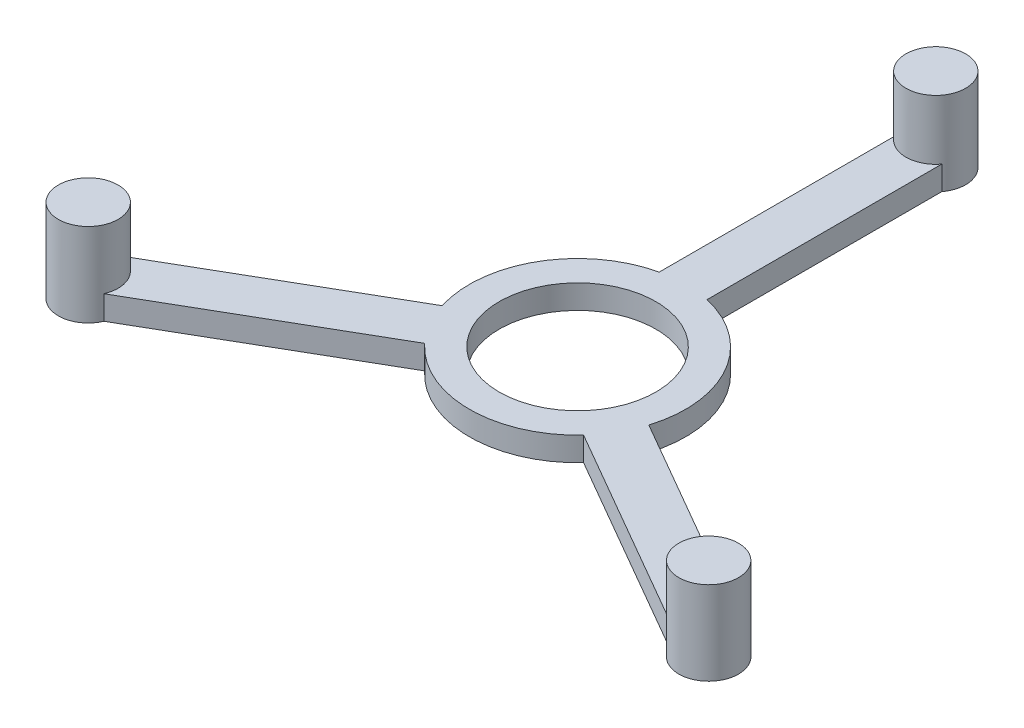
SolidWorks part; units mm, degrees
ref_plane "Front Plane" through (0, 0, 0) normal (0, 0, 1) x (1, 0, 0)
ref_plane "Top Plane" through (0, 0, 0) normal (0, 1, 0) x (1, 0, 0)
ref_plane "Right Plane" through (0, 0, 0) normal (1, 0, 0) x (0, 0, -1)
sketch "Sketch1" plane through (0, 0, 0) normal (0, 1, 0) x (1, 0, 0)
  line L0 (0, 0) -> (0, 38.1) construction
  line L1 (2.54, 11.2256) -> (2.54, 36.195)
  line L2 (-2.54, 11.2256) -> (-2.54, 36.195)
  line L3 (-2.54, 0) -> (-2.54, 38.1) construction
  line L4 (2.54, 0) -> (2.54, 38.1) construction
  circle A0 centre (0, 0) radius 8.3344
  arc A1 (-2.54, 11.2256) -> (2.54, 11.2256) centre (0, 0) ccw construction
  arc A2 (2.54, 36.195) -> (-2.54, 36.195) centre (0, 38.1) ccw
  arc A3 (-2.54, 11.2256) -> (2.54, 11.2256) centre (0, 0) ccw
  dimension "D1" = 16.6687
  dimension "D2" = 3.175
  dimension "D5" = 3.175
  dimension "D6" = 38.1
  dimension "D3" = 2.54
  dimension "D4" = 2.54
extrude "Boss-Extrude1" add sketch "Sketch1" along normal blind 2.54
sketch "Sketch3" plane through (0, 2.54, 0) normal (0, 1, 0) x (1, 0, 0)
  arc A1 (2.54, 36.195) -> (-2.54, 36.195) centre (0, 38.1) ccw construction
  arc A2 (2.54, 36.195) -> (-2.54, 36.195) centre (0, 38.1) ccw construction
  circle A3 centre (0, 38.1) radius 3.175
extrude "Boss-Extrude2" add sketch "Sketch3" along normal blind 6.35
sketch "Sketch2" plane through (0, 0, 0) normal (1, 0, 0) x (0, 0, -1)
  line L0 (0, 0) -> (0, 50000) construction
pattern_circular "CirPattern1" count 3 over 360 about axis through (0, 0, 0) along (0, 1, 0) of "Boss-Extrude1", "Boss-Extrude2"
